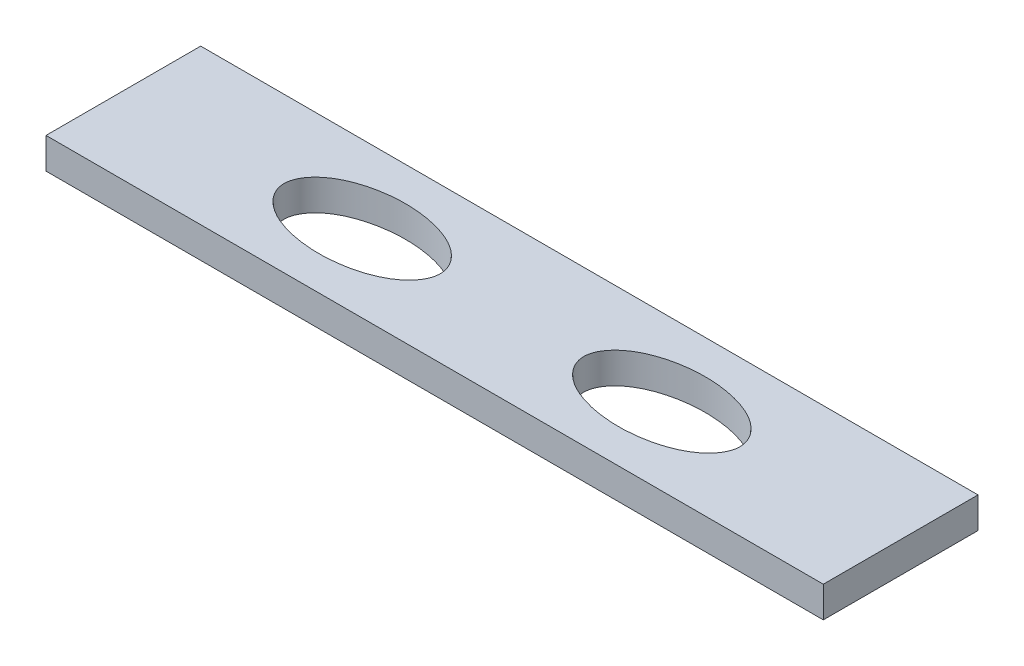
SolidWorks part; units mm, degrees
ref_plane "Front Plane" through (0, 0, 0) normal (0, 0, 1) x (1, 0, 0)
ref_plane "Top Plane" through (0, 0, 0) normal (0, 1, 0) x (1, 0, 0)
ref_plane "Right Plane" through (0, 0, 0) normal (1, 0, 0) x (0, 0, -1)
sketch "Sketch1" plane through (0, 0, 0) normal (0, 1, 0) x (1, 0, 0)
  line L0 (-38.2045, 1.7803) -> (12.0455, 1.7803) construction
  line L1 (-38.2045, 6.7803) -> (12.0455, 6.7803)
  line L2 (-38.2045, 6.7803) -> (-38.2045, -3.2197)
  line L3 (-38.2045, -3.2197) -> (12.0455, -3.2197)
  line L4 (12.0455, 6.7803) -> (12.0455, -3.2197)
  line L5 (-38.2045, 6.7803) -> (12.0455, -3.2197) construction
  line L6 (-38.2045, -3.2197) -> (12.0455, 6.7803) construction
  line L7 (-13.0795, -3.2197) -> (-13.0795, 6.7803) construction
  spline S1 degree 3 poles (-26.7035, 3.9889) (-28.3716, 1.7803) (-26.7035, -0.4283) (-22.7655, -1.3154) (-18.8276, -0.4283) (-17.1595, 1.7803) (-18.8276, 3.9889) (-22.7655, 4.876) (-26.7035, 3.9889) (-28.3716, 1.7803) (-26.7035, -0.4283) knots -2.356194 -1.570796 -0.785398 0 0.785398 1.570796 2.356194 3.141593 3.926991 4.712389 5.497787 6.283185 7.068583 7.853982 8.63938 only from (-27.8155, 1.7803) to (-27.8155, 1.7803)
  spline S3 degree 3 poles (-7.3315, 3.9889) (-8.9996, 1.7803) (-7.3315, -0.4283) (-3.3935, -1.3154) (0.5444, -0.4283) (2.2125, 1.7803) (0.5444, 3.9889) (-3.3935, 4.876) (-7.3315, 3.9889) (-8.9996, 1.7803) (-7.3315, -0.4283) knots -2.356194 -1.570796 -0.785398 0 0.785398 1.570796 2.356194 3.141593 3.926991 4.712389 5.497787 6.283185 7.068583 7.853982 8.63938 only from (-8.4435, 1.7803) to (-8.4435, 1.7803)
  point P0 (-13.0795, 1.7803)
  dimension "D1" = 10
  dimension "D2" = 50.25
extrude "Boss-Extrude1" add sketch "Sketch1" along normal blind 2
